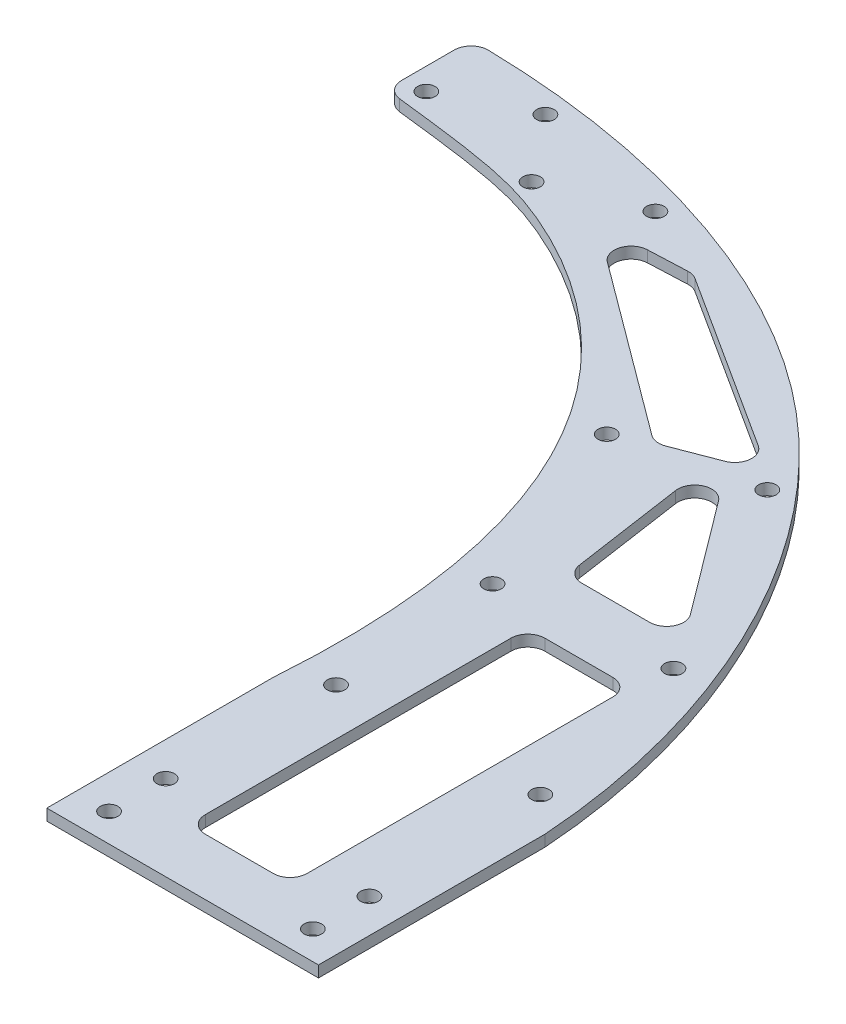
SolidWorks part; units mm, degrees
material "环氧树脂,未充填"
ref_plane "前视基准面" through (0, 0, 0) normal (0, 0, 1) x (1, 0, 0)
ref_plane "上视基准面" through (0, 0, 0) normal (0, 1, 0) x (1, 0, 0)
ref_plane "右视基准面" through (0, 0, 0) normal (1, 0, 0) x (0, 0, -1)
sketch "草图1" plane through (0, 0, 0) normal (0, 1, 0) x (1, 0, 0)
  line L0 (-80, 140) -> (-80, 155)
  line L1 (0, 0) -> (48, 0)
  line L2 (0, 0) -> (0, 40)
  line L3 (0, 40) -> (48, 40)
  line L4 (48, 0) -> (48, 40)
  spline S0 degree 3 poles (0, 40) (4.5148, 101.7081) (-40.6845, 134.9217) (-60.8865, 137.8387) (-80, 140) knots 0 0 0 0 0.623951 0.90472 0.90472 0.90472 0.90472
  spline S1 degree 3 poles (48, 40) (45.765, 73.2895) (16.0361, 137.6321) (-51.0623, 155.0467) (-80, 155) knots 0 0 0 0 0.537039 1 1 1 1
  dimension "D1" = 48
  dimension "D2" = 40
  dimension "D3" = 80
  dimension "D4" = 15
  dimension "D5" = 100
extrude "凸台-拉伸1" add sketch "草图1" along normal blind 2 contours L3 S1 L0 S0 | L1 L4 L3 L2
sketch "草图2" plane through (0, 2, 0) normal (0, 1, 0) x (1, 0, 0)
  line L0 (0, 10) -> (48, 10) construction
  line L1 (0, 0) -> (0, 40) construction
  line L2 (48, 0) -> (48, 40) construction
  line L3 (0, 0) -> (48, 0) construction
  line L4 (24, 0) -> (24, 20) construction
  line L6 (6, 5) -> (42, 5) construction
  line L7 (6, 5) -> (6, 15) construction
  line L8 (6, 15) -> (42, 15) construction
  line L9 (42, 5) -> (42, 15) construction
  line L10 (6, 5) -> (42, 15) construction
  line L11 (6, 15) -> (42, 5) construction
  circle A0 centre (6, 15) radius 1.55
  circle A1 centre (42, 15) radius 1.55
  circle A2 centre (42, 5) radius 1.55
  circle A3 centre (6, 5) radius 1.55
  point P10 (24, 10)
  dimension "D5" = 3.1
  dimension "D1" = 10
  dimension "D3" = 36
  dimension "D4" = 10
extrude "切除-拉伸1" cut sketch "草图2" against normal through all
sketch "草图3" plane through (0, 2, 0) normal (0, 1, 0) x (1, 0, 0)
  line L0 (24, 0) -> (24, 120.9063) construction
  line L1 (0, 0) -> (48, 0) construction
  line L3 (15, 10) -> (33, 10)
  line L4 (15, 10) -> (15, 70)
  line L5 (15, 70) -> (33, 70)
  line L6 (33, 10) -> (33, 70)
  line L7 (15, 10) -> (33, 70) construction
  line L8 (15, 70) -> (33, 10) construction
  point P4 (24, 40)
  dimension "D1" = 10
  dimension "D2" = 60
  dimension "D3" = 18
extrude "切除-拉伸2" cut sketch "草图3" against normal through all
fillet "圆角1" radius 3 4 edges at (33, 1, -70) (33, 1, -10) (15, 1, -10) (15, 1, -70)
sketch "草图4" plane through (0, 2, 0) normal (0, 1, 0) x (1, 0, 0)
  line L0 (5.2551, 115.7919) -> (30.8403, 81.6784)
  line L1 (30.8403, 81.6784) -> (10.2474, 81.6784)
  line L2 (5.2551, 115.7919) -> (10.2474, 81.6784)
extrude "切除-拉伸3" cut sketch "草图4" against normal through all
fillet "圆角2" radius 3 3 edges at (5.2551, 1, -115.7919) (10.2474, 1, -81.6784) (30.8403, 1, -81.6784)
sketch "草图5" plane through (0, 2, 0) normal (0, 1, 0) x (1, 0, 0)
  line L0 (-24.5877, 138.8183) -> (-40.8392, 138.1209)
  line L1 (-40.8392, 138.1209) -> (-2.2404, 109.4935)
  line L2 (-2.2404, 109.4935) -> (12.389, 115.1033)
  line L3 (12.389, 115.1033) -> (-24.5877, 138.8183)
extrude "切除-拉伸4" cut sketch "草图5" against normal through all
fillet "圆角3" radius 3 4 edges at (12.389, 1, -115.1033) (-2.2404, 1, -109.4935) (-24.5877, 1, -138.8183) (-40.8392, 1, -138.1209)
sketch "草图6" plane through (0, 2, 0) normal (0, 1, 0) x (1, 0, 0)
  circle A0 centre (-76.1183, 143.1699) radius 1.55
  circle A1 centre (-52.9985, 138.6487) radius 1.55
  circle A2 centre (-7.7306, 106.6781) radius 1.55
  circle A3 centre (5.0685, 73.6881) radius 1.55
  circle A4 centre (6.7029, 44.401) radius 1.55
  circle A5 centre (34.0002, 76.7134) radius 1.55
  circle A7 centre (41.522, 45.6694) radius 1.55
  circle A8 centre (14.9542, 112.3547) radius 1.55
  circle A9 centre (-37.5415, 145.0685) radius 1.55
  circle A10 centre (-62.067, 150.1597) radius 1.55
  dimension "D1" = 3.1
  dimension "D2" = 3.1
  dimension "D3" = 3.1
  dimension "D4" = 3.1
  dimension "D5" = 3.1
  dimension "D6" = 3.1
extrude "切除-拉伸5" cut sketch "草图6" against normal through all
fillet "圆角4" radius 3 2 edges at (-80, 1, -140) (-80, 1, -155)
